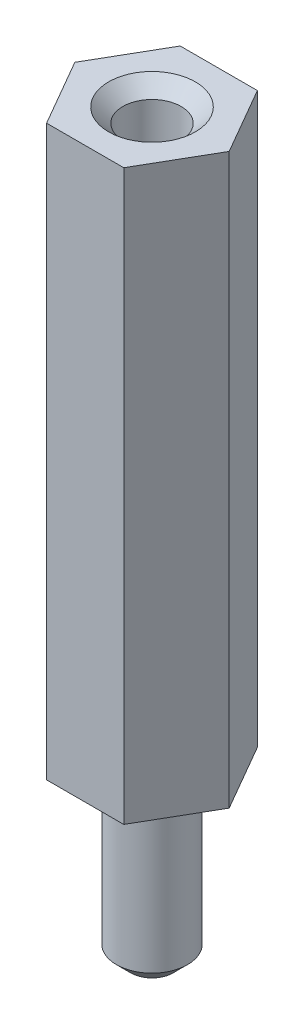
SolidWorks part; units mm, degrees
ref_plane "Front Plane" through (0, 0, 0) normal (0, 0, 1) x (1, 0, 0)
ref_plane "Top Plane" through (0, 0, 0) normal (0, 1, 0) x (1, 0, 0)
ref_plane "Right Plane" through (0, 0, 0) normal (1, 0, 0) x (0, 0, -1)
ref_plane "Plane1" through (0, 20, 0) normal (0, 1, 0) x (1, 0, 0)
sketch "Sketch1" plane through (0, 20, 0) normal (0, 1, 0) x (1, 0, 0)
  line L0 (1.3568, -2.35) -> (2.7135, 0)
  line L1 (2.7135, 0) -> (1.3568, 2.35)
  line L2 (1.3568, 2.35) -> (-1.3568, 2.35)
  line L3 (-1.3568, 2.35) -> (-2.7135, 0)
  line L4 (-2.7135, 0) -> (-1.3568, -2.35)
  line L5 (-1.3568, -2.35) -> (1.3568, -2.35)
  circle A0 centre (0, 0) radius 2.7135 construction
  point P9 (0, 0)
  point P10 (0, 0)
  point P11 (0, 0)
  point P12 (0, 0)
  point P13 (0, 0)
  dimension "D1" = 4.7
extrude "Boss-Extrude1" add sketch "Sketch1" against normal blind 20
ref_plane "Plane2" through (0, 0, 0) normal (0, 0, -1) x (-1, 0, 0)
sketch "Sketch2" plane through (0, 0, 0) normal (0, 0, -1) x (-1, 0, 0)
  line L0 (-1.25, -6) -> (0, -6)
  line L1 (0, -6) -> (0, 0)
  line L2 (0, 0) -> (-1.25, 0)
  line L3 (-1.25, 0) -> (-1.25, -6)
  line L4 (0, -6) -> (0, 0) construction
  line L5 (0, 0) -> (1.25, 0) construction
  point P4 (0, 0)
  dimension "D1" = 6
  dimension "D2" = 2.5
revolve "Revolve1" add sketch "Sketch2" angle 360 about L4
hole_wizard "Tap Drill for M2.5x0.45 Tap1" positions "Sketch4" profile "Sketch3" hole size "M2.5x0.45" standard "ANSI Metric"
sketch "Sketch4" plane through (0, 20, 0) normal (0, 1, 0) x (1, 0, 0)
  point P0 (0, 0)
sketch "Sketch3" plane through (0, 20, 0) normal (1, 0, 0) x (0, 0, 1)
  line L0 (0, 0) -> (0, 19)
  line L1 (0, 19) -> (1.025, 19)
  line L2 (1.025, 19) -> (1.025, 0)
  line L5 (1.025, 0) -> (0, 0)
  line L10 (0, 19) -> (-1.025, 19) construction
  line L11 (0, -6.35) -> (0, 107.95) construction
  dimension "Hole Dia." = 2.05
  dimension "Hole Depth" = 19
  dimension "Drill Angle" = 180
chamfer "Chamfer1" distance 0.5 angle 45 2 edges at (0, -6, 1.25) (0, 20, 1.025)
